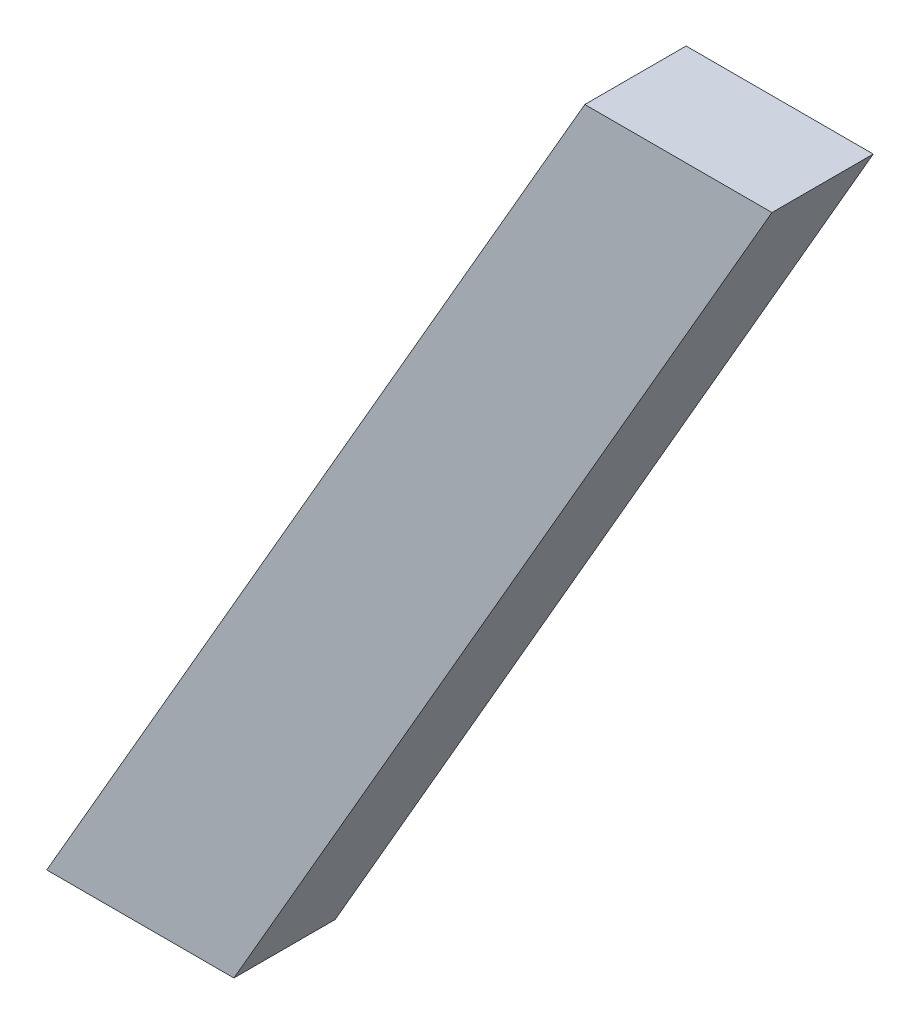
SolidWorks part; units mm, degrees
ref_plane "Plan de face" through (0, 0, 0) normal (0, 0, 1) x (1, 0, 0)
ref_plane "Plan de dessus" through (0, 0, 0) normal (0, 1, 0) x (1, 0, 0)
ref_plane "Plan de droite" through (0, 0, 0) normal (1, 0, 0) x (0, 0, -1)
sketch "Esquisse1" plane through (0, 0, 0) normal (0, 0, 1) x (1, 0, 0)
  line L0 (0, 0) -> (46.188, 0)
  line L1 (46.188, 0) -> (178.9786, 230)
  line L2 (178.9786, 230) -> (132.7906, 230)
  line L3 (132.7906, 230) -> (0, 0)
  dimension "D1" = 60
  dimension "D2" = 40
  dimension "D3" = 230
extrude "Boss.-Extru.1" add sketch "Esquisse1" along normal blind 25
